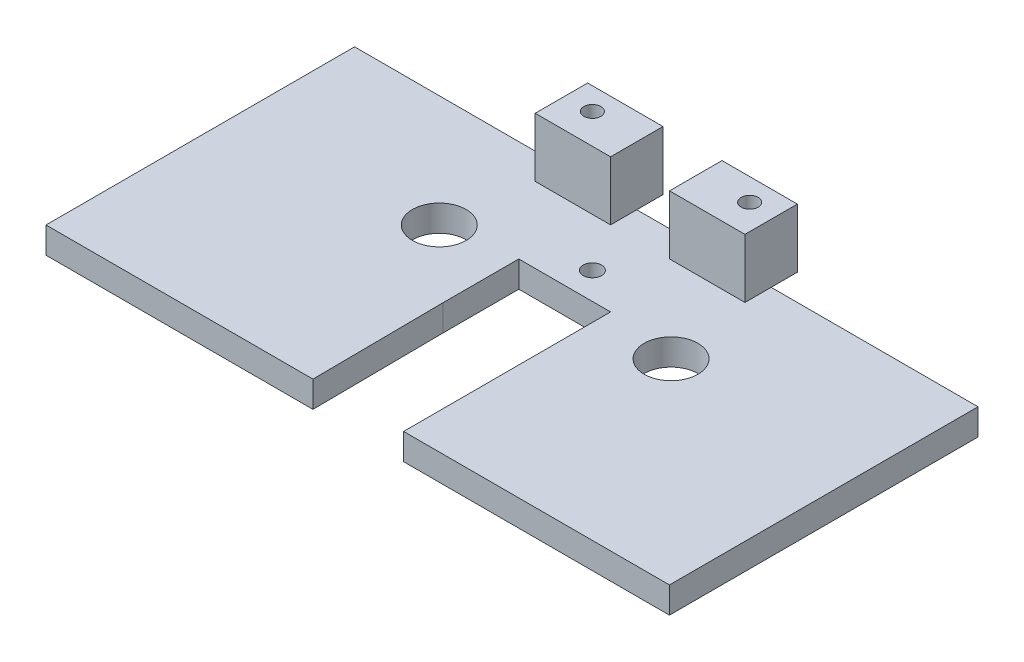
SolidWorks part; units mm, degrees
ref_plane "Front Plane" through (0, 0, 0) normal (0, 0, 1) x (1, 0, 0)
ref_plane "Top Plane" through (0, 0, 0) normal (0, 1, 0) x (1, 0, 0)
ref_plane "Right Plane" through (0, 0, 0) normal (1, 0, 0) x (0, 0, -1)
sketch "Sketch2" plane through (0, 0, 0) normal (0, 1, 0) x (1, 0, 0)
  line L0 (-3.5, -6.7693) -> (-3.5, -0.9807)
  line L1 (-13.7785, -6.7693) -> (-3.5, -6.7693)
  line L2 (-13.7785, -6.7693) -> (-13.7785, 6.7693)
  line L3 (-13.7785, 6.7693) -> (13.7785, 6.7693)
  line L4 (13.7785, -6.7693) -> (13.7785, 6.7693)
  line L5 (-13.7785, -6.7693) -> (13.7785, 6.7693) construction
  line L6 (-13.7785, 6.7693) -> (13.7785, -6.7693) construction
  line L7 (-3.5, -0.9807) -> (3.5, -0.9807)
  line L8 (3.5, -0.9807) -> (3.5, -6.7693)
  line L9 (3.5, -6.7693) -> (13.7785, -6.7693)
  line L10 (-8.7785, -1.7693) -> (8.7785, -1.7693) construction
  circle A0 centre (-8.7785, -1.7693) radius 2.05
  circle A1 centre (8.9015, -1.7693) radius 2.05
  circle A2 centre (0.0585, 1.074) radius 0.7006
  point P0 (0, 0)
  point P9 (0, -0.9807)
  point P17 (0, -1.7693)
  dimension "D5" = 4.1
  dimension "D6" = 1.4013
  dimension "D1" = 27.557
  dimension "D2" = 13.5386
  dimension "D3" = 5.7886
  dimension "D4" = 7
  dimension "D7" = 17.68
  dimension "D8" = 5.6953
  dimension "D9" = 5
  dimension "D10" = 13.72
extrude "Boss-Extrude1" add sketch "Sketch2" along normal blind 2
sketch "Sketch3" plane through (0, 2, 0) normal (0, 1, 0) x (1, 0, 0)
  line L0 (13.7785, 6.7693) -> (-13.7785, 6.7693) construction
  line L1 (-8, 4.7693) -> (-2.25, 4.7693)
  line L2 (-8, 4.7693) -> (-8, 8.7693)
  line L3 (-8, 8.7693) -> (-2.25, 8.7693)
  line L4 (-2.25, 4.7693) -> (-2.25, 8.7693)
  line L5 (-8, 4.7693) -> (-2.25, 8.7693) construction
  line L6 (-8, 8.7693) -> (-2.25, 4.7693) construction
  line L7 (-2.25, 8.7693) -> (2.25, 8.7693) construction
  line L8 (2.25, 4.7693) -> (8, 4.7693)
  line L9 (2.25, 4.7693) -> (2.25, 8.7693)
  line L10 (2.25, 8.7693) -> (8, 8.7693)
  line L11 (8, 4.7693) -> (8, 8.7693)
  line L12 (2.25, 4.7693) -> (8, 8.7693) construction
  line L13 (2.25, 8.7693) -> (8, 4.7693) construction
  point P0 (-5.125, 6.7693)
  point P7 (5.125, 6.7693)
  point P12 (0, 6.7693)
  point P13 (0, 8.7693)
  dimension "D1" = 5.75
  dimension "D2" = 4
  dimension "D3" = 4.5
extrude "Boss-Extrude2" add sketch "Sketch3" along normal blind 4.5
sketch "Sketch4" plane through (0, 6.5, 0) normal (0, 1, 0) x (1, 0, 0)
  line L0 (8, 4.7693) -> (8, 8.7693) construction
  line L2 (-8, 8.7693) -> (-8, 4.7693) construction
  line L3 (-8, 4.7693) -> (-2.25, 4.7693) construction
  circle A0 centre (-5.94, 7.0693) radius 0.65
  circle A1 centre (6.06, 7.0693) radius 0.65
  dimension "D2" = 1.3
  dimension "D1" = 2.06
  dimension "D3" = 2.3
  dimension "D4" = 1.94
extrude "Cut-Extrude1" cut sketch "Sketch4" against normal through all
sketch "Sketch5" plane through (0, 2, 0) normal (0, 1, 0) x (1, 0, 0)
  line L0 (-13.7785, 6.7693) -> (-23.7785, 6.7693)
  line L1 (-23.7785, 6.7693) -> (-23.7785, -16.7689)
  line L2 (-23.7785, -16.7689) -> (-3.4139, -16.7689)
  line L3 (-3.4139, -16.7689) -> (-3.5, -6.7693)
  line L4 (-3.5, -6.7693) -> (-13.7785, -6.7693)
  line L5 (-13.7785, -6.7693) -> (-13.7785, 6.7693)
  line L6 (3.5, -6.7693) -> (3.5, -16.7689)
  line L7 (3.5, -16.7689) -> (23.7785, -16.7689)
  line L8 (23.7785, -16.7689) -> (23.7785, 6.7693)
  line L9 (23.7785, 6.7693) -> (13.7785, 6.7693)
  line L10 (13.7785, 6.7693) -> (13.7785, -6.7693)
  line L11 (13.7785, -6.7693) -> (3.5, -6.7693)
  dimension "D1" = 10
  dimension "D2" = 10
extrude "Boss-Extrude3" add sketch "Sketch5" against normal up to surface (2 mm away) up to face at (0.02, 0, -0.9064)
